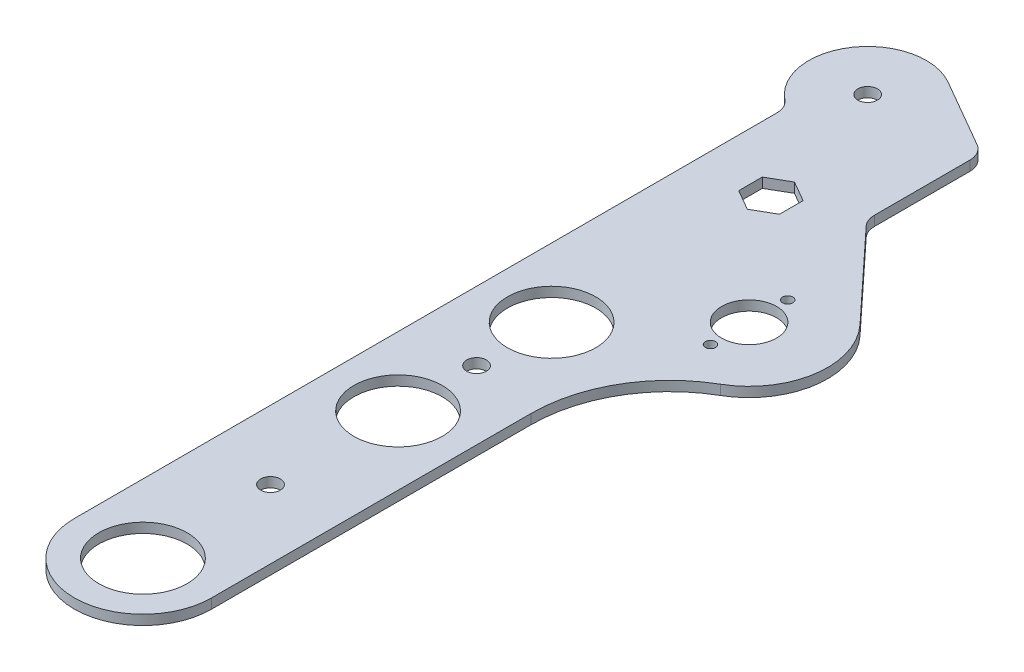
SolidWorks part; units mm, degrees
material "6061-T6 (SS)"
ref_plane "Front Plane" through (0, 0, 0) normal (0, 0, 1) x (1, 0, 0)
ref_plane "Top Plane" through (0, 0, 0) normal (0, 1, 0) x (1, 0, 0)
ref_plane "Right Plane" through (0, 0, 0) normal (1, 0, 0) x (0, 0, -1)
sketch "Sketch1" plane through (0, 0, 0) normal (0, 1, 0) x (1, 0, 0)
  line L2 (0, 24.1662) -> (0, -203.2)
  line L5 (22.225, -7.6256) -> (28.829, -3.8128)
  line L6 (28.829, -3.8128) -> (28.829, 3.8128)
  line L7 (28.829, 3.8128) -> (22.225, 7.6256)
  line L8 (22.225, 7.6256) -> (15.621, 3.8128)
  line L9 (15.621, 3.8128) -> (15.621, -3.8128)
  line L10 (15.621, -3.8128) -> (22.225, -7.6256)
  line L12 (22.225, -11.6625) -> (22.225, 61.481) construction
  line L13 (16.0106, -10.7637) -> (25016.0106, 43290.5065) construction
  line L14 (52.138, 12.0591) -> (43353.4081, -24987.9409) construction
  line L15 (56.922, 9.297) -> (31.522, -34.697) construction
  line L16 (56.922, 9.297) -> (-163.0484, 136.297) construction
  line L17 (31.522, -34.697) -> (-188.4484, 92.303) construction
  line L18 (-163.0484, 136.297) -> (-188.4484, 92.303) construction
  line L26 (19.05, 60.4919) -> (41.275, 47.6603)
  line L27 (44.45, 11.2344) -> (44.45, 42.161)
  line L28 (19.05, 60.4919) -> (9.525, 43.9941) construction
  line L29 (72.7757, -21.7174) -> (46.1503, 6.9098)
  line L30 (44.45, -99.8572) -> (44.45, -203.2)
  line L31 (44.45, 8.7379) -> (38.4991, 15.1362) construction
  arc A1 (0, -203.2) -> (44.45, -203.2) centre (22.225, -203.2) ccw
  circle A2 centre (22.225, -203.2) radius 14.2875
  circle A4 centre (22.225, -120.65) radius 14.2875
  circle A5 centre (22.225, 0) radius 6.604 construction
  circle A6 centre (22.225, -70.9676) radius 14.2875
  arc A11 (19.05, 60.4919) -> (-2.3812, 29.1232) centre (9.525, 43.9941) ccw
  circle A12 centre (22.225, -95.25) radius 3.175
  circle A13 centre (22.225, -161.925) radius 3.175
  circle A14 centre (9.525, 43.9941) radius 6.35 construction
  circle A15 centre (9.525, 43.9941) radius 3.175
  circle A16 centre (22.225, 0) radius 22.225 construction
  circle A17 centre (54.1768, -39.0158) radius 8.89
  arc A18 (66.8768, -61.0129) -> (72.7757, -21.7174) centre (54.1768, -39.0158) ccw
  arc A19 (66.8768, -61.0129) -> (44.45, -99.8572) centre (89.3035, -99.8572) ccw
  arc A20 (0, 24.1662) -> (-2.3812, 29.1232) centre (-6.35, 24.1662) ccw
  arc A21 (41.275, 47.6603) -> (44.45, 42.161) centre (38.1, 42.161) cw
  arc A22 (44.45, 11.2344) -> (46.1503, 6.9098) centre (50.8, 11.2344) ccw
  circle A23 centre (54.1768, -39.0158) radius 12.5 construction
  circle A24 centre (54.1768, -51.5158) radius 1.65
  circle A25 centre (54.1768, -26.5158) radius 1.65
  point P30 (0, 0)
  point P57 (22.225, 22.225)
  point P64 (0, 27.4963)
  dimension "D3" = 13.208
  dimension "D4" = 28.575
  dimension "D7" = 17.78
  dimension "D8" = 25
  dimension "D9" = 3.3
  dimension "D11" = 12.7
  dimension "D12" = 30
  dimension "D13" = 90
  dimension "D18" = 6.35
  dimension "D19" = 38.1
  dimension "D23" = 6.35
  dimension "D26" = 50.8
  dimension "D28" = 60
  dimension "D29" = 6.35
  dimension "D5" = 82.55
  dimension "D6" = 49.6824
  dimension "D10" = 44.45
  dimension "D14" = 25.4
  dimension "D15" = 25.4
  dimension "D16" = 50.8
  dimension "D17" = 254
  dimension "D20" = 120
  dimension "D21" = 41.275
  dimension "D22" = 25.4
  dimension "D24" = 45.1866
  dimension "D25" = 45
  dimension "D27" = 203.2
extrude "Boss-Extrude1" add sketch "Sketch1" along normal blind 3.175
